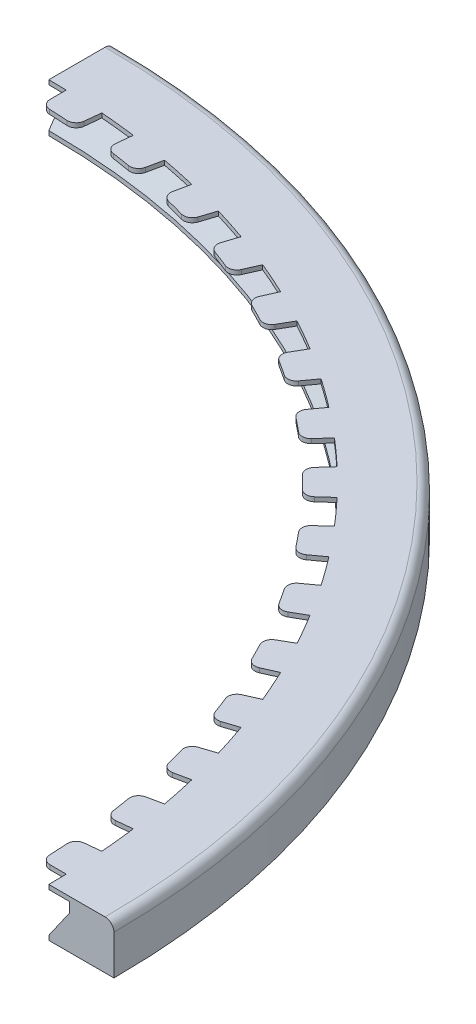
SolidWorks part; units mm, degrees
material "ABS"
ref_plane "Front" through (0, 0, 0) normal (0, 0, 1) x (1, 0, 0)
ref_plane "Top" through (0, 0, 0) normal (0, 1, 0) x (1, 0, 0)
ref_plane "Right" through (0, 0, 0) normal (1, 0, 0) x (0, 0, -1)
sketch "Sketch1" plane through (0, 0, 0) normal (0, 0, 1) x (1, 0, 0)
  line L0 (0, 0) -> (0, 16.9089) construction
  line L1 (-157.75, -10.97) -> (-157.75, -9.97)
  line L2 (-157.75, -9.97) -> (-162.5, -3.1863)
  line L3 (-162.5, -3.1863) -> (-162.5, -1)
  line L4 (-162.5, -1) -> (-152.165, -1)
  line L5 (-152.165, -1) -> (-152.165, 0)
  line L6 (-152.165, 0) -> (-172.5, 0)
  line L7 (-172.5, 0) -> (-172.5, -10.97)
  line L10 (-157.75, -10.97) -> (-172.5, -10.97)
  dimension "D1" = 20.335
  dimension "D2" = 345
  dimension "D3" = 1
  dimension "D4" = 10
  dimension "D5" = 145
  dimension "D6" = 1
  dimension "D7" = 14.75
  dimension "D8" = 9.97
revolve "Revolve1" add sketch "Sketch1" angle 360 about L0
sketch "Sketch2" plane through (0, 0, 0) normal (0, 1, 0) x (1, 0, 0)
  line L0 (0, 157.75) -> (0, 150.6993) construction
  line L1 (-4, 150.6993) -> (4, 150.6993)
  line L2 (-4, 150.6993) -> (-4, 157.6993)
  line L3 (4, 150.6993) -> (4, 157.6993)
  arc A0 (4, 157.6993) -> (-4, 157.6993) centre (0, 0) ccw
  point P7 (0, 150.6993)
  dimension "D2" = 8
  dimension "D1" = 315.5
  dimension "D3" = 7
extrude "Cut-Extrude1" cut sketch "Sketch2" against normal through all both and the other way through all
pattern_circular "CirPattern1" count 60 over 360 about axis through (0, 0, 0) along (0, 1, 0) of "Cut-Extrude1"
sketch "Sketch6" plane through (0, 0, 0) normal (0, 1, 0) x (1, 0, 0)
  line L1 (0, 0) -> (0, 216.3055)
  line L2 (0, 0) -> (216.3055, 0)
  arc A0 (0, 216.3055) -> (216.3055, 0) centre (0, 0) ccw
  point P57 (0, 0)
extrude "Cut-Extrude2" cut sketch "Sketch6" against normal mid plane 50.8
fillet "Fillet1" radius 2 30 edges at (104.7557, -0.5, -110.365) (98.8105, -0.5, -115.7181) (92.6455, -0.5, -120.7104) (86.1734, -0.5, -125.4127) (79.5203, -0.5, -129.7332) (72.5921, -0.5, -133.7332) (65.5239, -0.5, -137.3347) (58.2155, -0.5, -140.5886) (50.8095, -0.5, -143.4314) (43.2011, -0.5, -145.9036) (35.5385, -0.5, -147.9567) (27.7134, -0.5, -149.62) (19.8782, -0.5, -150.861) (11.922, -0.5, -151.6972) (4, -0.5, -152.1124) (152.1124, -0.5, -4) (151.6972, -0.5, -11.922) (150.861, -0.5, -19.8782) (149.62, -0.5, -27.7134) (147.9567, -0.5, -35.5385) (145.9036, -0.5, -43.2011) (143.4314, -0.5, -50.8095) (140.5886, -0.5, -58.2155) (137.3347, -0.5, -65.5239) (133.7332, -0.5, -72.5921) (129.7332, -0.5, -79.5203) (125.4127, -0.5, -86.1734) (120.7104, -0.5, -92.6455) (115.7181, -0.5, -98.8105) (110.365, -0.5, -104.7557)
hole_wizard "#6 (0.204) Diameter Hole1" positions "Sketch7" profile "Sketch8" hole size "#6" standard "ANSI Inch"
sketch "Sketch7" plane through (0, -10.97, 0) normal (0, -1, 0) x (-1, 0, 0)
  line L0 (-172.5, 0) -> (0, 0) construction
  line L1 (0, 0) -> (0, 172.5) construction
  line L2 (-155.2118, 64.2908) -> (0, 0) construction
  line L3 (0, 0) -> (-64.2908, 155.2118) construction
  line L4 (-77.6059, 32.1454) -> (-86.25, 0) construction
  line L5 (-32.1454, 77.6059) -> (0, 86.25) construction
  line L6 (0, 157.75) -> (0, 172.5) construction
  circle A0 centre (0, 0) radius 168 construction
  arc A1 (0, 172.5) -> (-172.5, 0) centre (0, 0) ccw construction
  point P10 (-155.2118, 64.2908)
  point P17 (-64.2908, 155.2118)
  point P24 (-67.9719, 67.9719)
  dimension "D2" = 336
  dimension "D1" = 45
sketch "Sketch8" plane through (64.2908, -10.97, -155.2118) normal (1, 0, 0) x (0, 0, -1)
  line L0 (0, 0) -> (0, 9.2973)
  line L1 (0, 9.2973) -> (2.159, 8)
  line L2 (2.159, 8) -> (2.159, 0)
  line L5 (2.159, 0) -> (0, 0)
  line L10 (0, 9.2973) -> (-2.159, 8) construction
  line L11 (0, -6.35) -> (0, 107.95) construction
  dimension "Hole Dia." = 4.318
  dimension "Hole Depth" = 8
  dimension "Drill Angle" = 118
fillet "Fillet2" radius 2 1 edges at (121.9759, 0, -121.9759)
